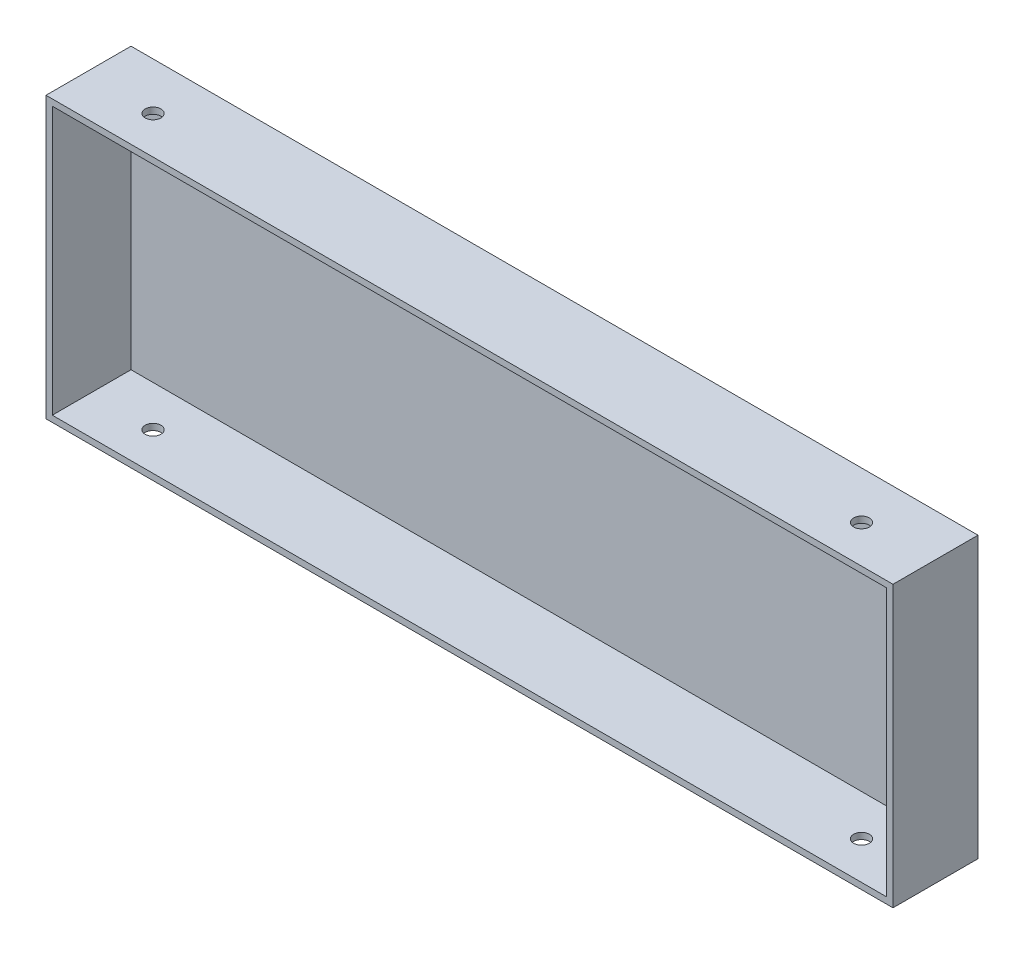
SolidWorks part; units mm, degrees
ref_plane "Front Plane" through (0, 0, 0) normal (0, 0, 1) x (1, 0, 0)
ref_plane "Top Plane" through (0, 0, 0) normal (0, 1, 0) x (1, 0, 0)
ref_plane "Right Plane" through (0, 0, 0) normal (1, 0, 0) x (0, 0, -1)
sketch "Sketch1" plane through (0, 0, 0) normal (0, 0, 1) x (1, 0, 0)
  line L1 (0, 0) -> (265, 0)
  line L2 (0, 0) -> (0, 85)
  line L3 (0, 85) -> (265, 85)
  line L4 (265, 0) -> (265, 85)
  dimension "D1" = 265
  dimension "D2" = 85
extrude "Boss-Extrude2" add sketch "Sketch1" along normal blind 25 contours L3 L4 L1 L2
shell "Shell1" thickness 2
ref_plane "Plane2" through (0, 42.5, 0) normal (0, 1, 0) x (1, 0, 0)
sketch "Sketch3" plane through (0, 42.5, 0) normal (0, 1, 0) x (1, 0, 0)
  line L5 (-2, 2) -> (267, 2) construction
  line L6 (107.5, 2) -> (157.5, 2)
  line L7 (107.5, 2) -> (107.5, 22)
  line L8 (107.5, 22) -> (157.5, 22)
  line L9 (157.5, 2) -> (157.5, 22)
  point P4 (132.5, 2)
  point P7 (132.5, 2)
  dimension "D1" = 20
  dimension "D2" = 50
extrude "Boss-Extrude3" add sketch "Sketch3" along normal mid plane 2
sketch "Sketch5" plane through (0, 87, 0) normal (0, 1, 0) x (1, 0, 0)
  line L0 (-2, 2) -> (267, 2) construction
  line L1 (267, -25) -> (267, 2) construction
  line L2 (-2, -25) -> (-2, 2) construction
  circle A0 centre (245, -13) radius 2.5
  circle A1 centre (20, -13) radius 2.5
  dimension "D1" = 5
  dimension "D2" = 15
  dimension "D4" = 5
  dimension "D5" = 22
  dimension "D6" = 15
  dimension "D3" = 22
extrude "Cut-Extrude1" cut sketch "Sketch5" against normal up to surface (87 mm away)
mirror "Mirror1" about plane through (0, 42.5, 0) normal (0, 1, 0) of "Cut-Extrude1"
